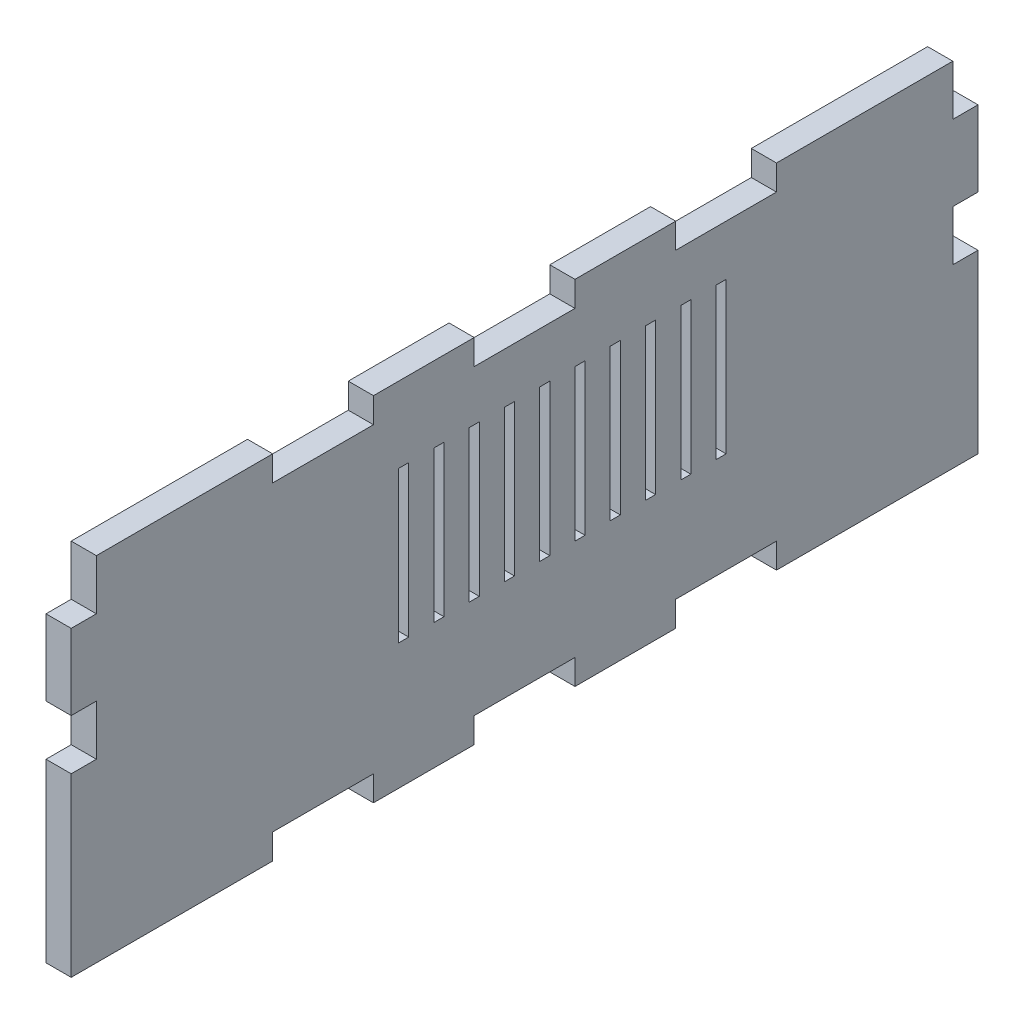
SolidWorks part; units mm, degrees
ref_plane "Plan de face" through (0, 0, 0) normal (0, 0, 1) x (1, 0, 0)
ref_plane "Plan de dessus" through (0, 0, 0) normal (0, 1, 0) x (1, 0, 0)
ref_plane "Plan de droite" through (0, 0, 0) normal (1, 0, 0) x (0, 0, -1)
sketch "Esquisse1" plane through (0, 0, 0) normal (1, 0, 0) x (0, 0, -1)
  line L1 (-90, 35) -> (90, 35)
  line L2 (-90, 35) -> (-90, -35)
  line L3 (-90, -35) -> (90, -35)
  line L4 (90, 35) -> (90, -35)
  line L5 (-90, 35) -> (90, -35) construction
  line L6 (-90, -35) -> (90, 35) construction
  point P0 (0, 0)
  dimension "D1" = 70
  dimension "D2" = 180
extrude "Boss.-Extru.1" add sketch "Esquisse1" along normal blind 5
sketch "Esquisse3" plane through (5, 0, 0) normal (1, 0, 0) x (0, 0, -1)
  line L0 (-90, 35) -> (-90, -35) construction
  line L1 (-90, 35) -> (-85, 35)
  line L2 (-90, 35) -> (-90, 25)
  line L3 (-90, 25) -> (-85, 25)
  line L4 (-85, 35) -> (-85, 25)
  line L5 (-90, 10) -> (-85, 10)
  line L6 (-90, 10) -> (-90, 0)
  line L7 (-90, 0) -> (-85, 0)
  line L8 (-85, 10) -> (-85, 0)
  line L9 (90, -35) -> (90, 35) construction
  line L10 (90, 35) -> (85, 35)
  line L11 (90, 35) -> (90, 25)
  line L12 (90, 25) -> (85, 25)
  line L13 (85, 35) -> (85, 25)
  line L14 (90, 0) -> (85, 0)
  line L15 (90, 0) -> (90, 10)
  line L16 (90, 10) -> (85, 10)
  line L17 (85, 0) -> (85, 10)
  line L18 (90, 35) -> (-90, 35) construction
  line L19 (-50, 35) -> (-30, 35)
  line L20 (-50, 35) -> (-50, 30)
  line L21 (-50, 30) -> (-30, 30)
  line L22 (-30, 35) -> (-30, 30)
  line L24 (30, 35) -> (50, 35)
  line L25 (30, 35) -> (30, 30)
  line L26 (30, 30) -> (50, 30)
  line L27 (50, 35) -> (50, 30)
  line L28 (-10, 35) -> (10, 35)
  line L29 (-10, 35) -> (-10, 30)
  line L30 (-10, 30) -> (10, 30)
  line L31 (10, 35) -> (10, 30)
  line L32 (-90, -35) -> (90, -35) construction
  line L33 (-50, -35) -> (-30, -35)
  line L34 (-50, -35) -> (-50, -30)
  line L35 (-50, -30) -> (-30, -30)
  line L36 (-30, -35) -> (-30, -30)
  line L38 (-10, -35) -> (10, -35)
  line L39 (-10, -35) -> (-10, -30)
  line L40 (-10, -30) -> (10, -30)
  line L41 (10, -35) -> (10, -30)
  line L42 (30, -35) -> (50, -35)
  line L43 (30, -35) -> (30, -30)
  line L44 (30, -30) -> (50, -30)
  line L45 (50, -35) -> (50, -30)
  point P37 (0, 30)
  dimension "D1" = 5
  dimension "D2" = 10
  dimension "D3" = 5
  dimension "D4" = 10
  dimension "D5" = 15
  dimension "D6" = 10
  dimension "D7" = 5
  dimension "D8" = 5
  dimension "D9" = 10
  dimension "D10" = 15
  dimension "D11" = 5
  dimension "D12" = 20
  dimension "D13" = 20
  dimension "D14" = 20
  dimension "D15" = 20
  dimension "D16" = 20
  dimension "D17" = 5
extrude "Enlèv. mat.-Extru.2" cut sketch "Esquisse3" against normal blind 5
sketch "Esquisse4" plane through (5, 0, 0) normal (1, 0, 0) x (0, 0, -1)
  line L0 (31, 20) -> (31, -10)
  line L1 (38, 20) -> (40, 20)
  line L2 (38, 20) -> (38, -10)
  line L3 (38, -10) -> (40, -10)
  line L4 (40, 20) -> (40, -10)
  line L5 (31, 20) -> (33, 20)
  line L6 (33, 20) -> (33, -10)
  line L7 (31, -10) -> (33, -10)
  line L8 (24, 20) -> (24, -10)
  line L9 (24, 20) -> (26, 20)
  line L10 (26, 20) -> (26, -10)
  line L11 (24, -10) -> (26, -10)
  line L12 (17, 20) -> (17, -10)
  line L13 (17, 20) -> (19, 20)
  line L14 (19, 20) -> (19, -10)
  line L15 (17, -10) -> (19, -10)
  line L16 (10, 20) -> (10, -10)
  line L17 (10, 20) -> (12, 20)
  line L18 (12, 20) -> (12, -10)
  line L19 (10, -10) -> (12, -10)
  line L20 (3, 20) -> (3, -10)
  line L21 (3, 20) -> (5, 20)
  line L22 (5, 20) -> (5, -10)
  line L23 (3, -10) -> (5, -10)
  line L24 (-4, 20) -> (-4, -10)
  line L25 (-4, 20) -> (-2, 20)
  line L26 (-2, 20) -> (-2, -10)
  line L27 (-4, -10) -> (-2, -10)
  line L28 (-11, 20) -> (-11, -10)
  line L29 (-11, 20) -> (-9, 20)
  line L30 (-9, 20) -> (-9, -10)
  line L31 (-11, -10) -> (-9, -10)
  line L32 (-18, 20) -> (-18, -10)
  line L33 (-18, 20) -> (-16, 20)
  line L34 (-16, 20) -> (-16, -10)
  line L35 (-18, -10) -> (-16, -10)
  line L36 (-25, 20) -> (-25, -10)
  line L37 (-25, 20) -> (-23, 20)
  line L38 (-23, 20) -> (-23, -10)
  line L39 (-25, -10) -> (-23, -10)
  line L40 (90, -35) -> (90, 0) construction
  line L41 (-10, 30) -> (10, 30) construction
  dimension "D1" = 2
  dimension "D2" = 30
  dimension "D4" = 50
  dimension "D5" = 10
  dimension "D6" = 5
  dimension "D3" = 10
extrude "Enlèv. mat.-Extru.3" cut sketch "Esquisse4" against normal blind 5
